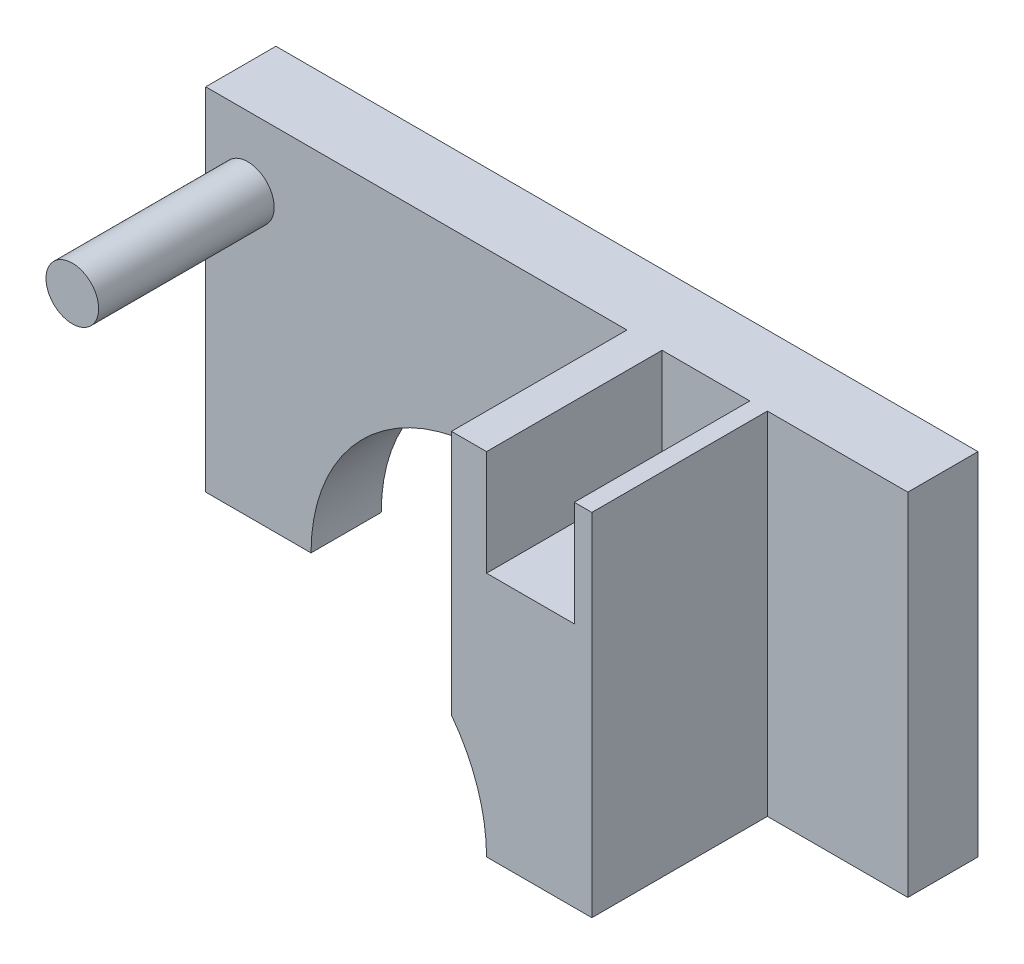
SolidWorks part; units mm, degrees
ref_plane "Přední rovina" through (0, 0, 0) normal (0, 0, 1) x (1, 0, 0)
ref_plane "Horní rovina" through (0, 0, 0) normal (0, 1, 0) x (1, 0, 0)
ref_plane "Pravá rovina" through (0, 0, 0) normal (1, 0, 0) x (0, 0, -1)
sketch "Skica1" plane through (0, 0, 0) normal (0, 0, 1) x (1, 0, 0)
  line L1 (0, 0) -> (200, 0)
  line L2 (0, 0) -> (0, 100)
  line L3 (0, 100) -> (200, 100)
  line L4 (200, 0) -> (200, 100)
  dimension "D1" = 100
  dimension "D2" = 200
extrude "Přidat vysunutím1" add sketch "Skica1" along normal blind 20
sketch "Skica2" plane through (0, 0, 20) normal (0, 0, 1) x (1, 0, 0)
  line L0 (0, 0) -> (200, 0) construction
  line L1 (120, 0) -> (160, 0)
  line L2 (120, 0) -> (120, 100)
  line L3 (120, 100) -> (130, 100)
  line L4 (160, 0) -> (160, 100)
  line L5 (200, 100) -> (0, 100) construction
  line L6 (0, 100) -> (0, 0) construction
  line L7 (155, 100) -> (160, 100)
  line L9 (130, 100) -> (130, 70)
  line L10 (130, 70) -> (155, 70)
  line L11 (155, 100) -> (155, 70)
  point P15 (0, 0)
  dimension "D1" = 120
  dimension "D2" = 40
  dimension "D3" = 10
  dimension "D4" = 5
  dimension "D5" = 30
extrude "Přidat vysunutím2" add sketch "Skica2" along normal blind 50 contours L9 L10 L11 L7 L4 L1 L2 L3
sketch "Skica4" plane through (0, 0, 0) normal (0, 0, -1) x (-1, 0, 0)
  line L0 (0, 0) -> (-200, 0) construction
  circle A0 centre (-80, 0) radius 50
  dimension "D1" = 100
  dimension "D2" = 80
extrude "Odebrat vysunutím1" cut sketch "Skica4" against normal up to surface (70 mm away) up to face at (141.25, 67.5, 70)
sketch "Skica7" plane through (0, 0, 20) normal (0, 0, 1) x (1, 0, 0)
  line L0 (120, 100) -> (0, 100) construction
  line L2 (0, 100) -> (0, 0) construction
  circle A0 centre (12, 80) radius 7.5
  point P2 (0, 0)
  point P7 (0, 72.8608)
  point P8 (19.4389, 72.7656)
  dimension "D1" = 15
  dimension "D2" = 20
  dimension "D3" = 12
extrude "Přidat vysunutím3" add sketch "Skica7" along normal blind 50
